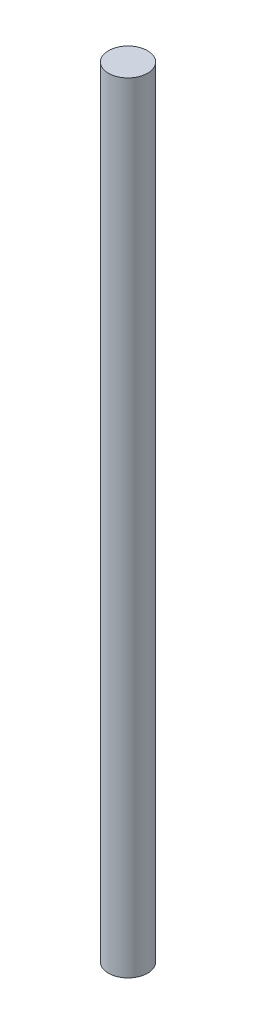
SolidWorks part; units mm, degrees
ref_plane "Plano frontal" through (0, 0, 0) normal (0, 0, 1) x (1, 0, 0)
ref_plane "Plano superior" through (0, 0, 0) normal (0, 1, 0) x (1, 0, 0)
ref_plane "Plano direito" through (0, 0, 0) normal (1, 0, 0) x (0, 0, -1)
sketch "Esboço1" plane through (0, 0, 0) normal (0, 0, 1) x (1, 0, 0)
  line L0 (0, 0) -> (0, 1561.37) construction
  line L1 (0, 1561.37) -> (39.18, 1561.37)
  line L2 (39.18, 1561.37) -> (39.18, 0)
  line L3 (39.18, 0) -> (0, 0)
  line L4 (0, 0) -> (0, 1561.37)
  dimension "D1" = 1561.37
  dimension "D2" = 39.18
revolve "Revolução1" add sketch "Esboço1" angle 360 about L0
